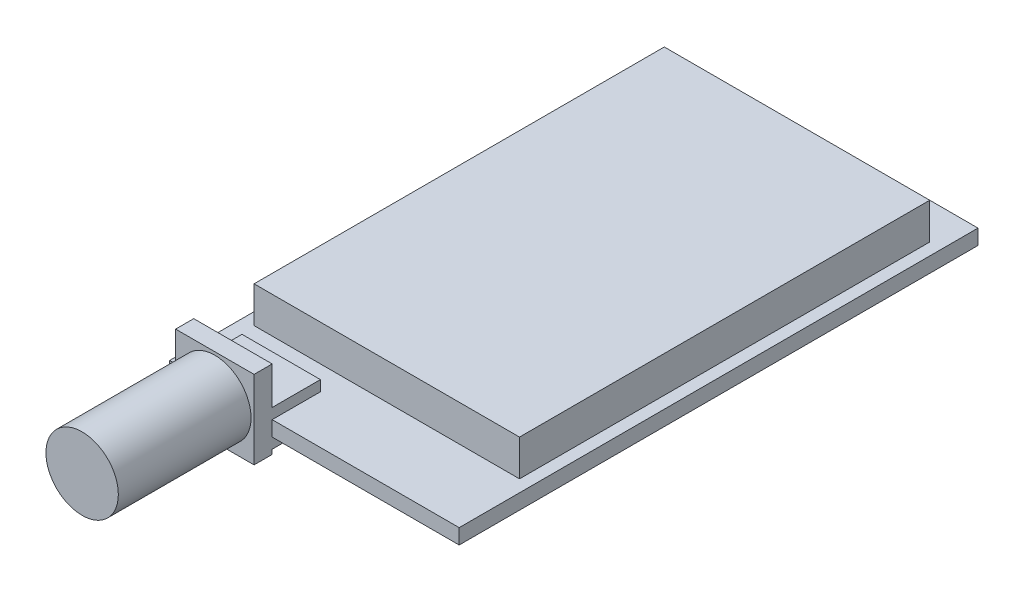
SolidWorks part; units mm, degrees
ref_plane "Front Plane" through (0, 0, 0) normal (0, 0, 1) x (1, 0, 0)
ref_plane "Top Plane" through (0, 0, 0) normal (0, 1, 0) x (1, 0, 0)
ref_plane "Right Plane" through (0, 0, 0) normal (1, 0, 0) x (0, 0, -1)
sketch "Sketch1" plane through (0, 0, 0) normal (0, 1, 0) x (1, 0, 0)
  line L1 (-12, 21.5) -> (12, 21.5)
  line L2 (-12, 21.5) -> (-12, -21.5)
  line L3 (-12, -21.5) -> (12, -21.5)
  line L4 (12, 21.5) -> (12, -21.5)
  line L5 (-12, 21.5) -> (12, -21.5) construction
  line L6 (-12, -21.5) -> (12, 21.5) construction
  point P0 (0, 0)
  dimension "D1" = 43
  dimension "D2" = 24
extrude "PCB" add sketch "Sketch1" along normal blind 1.25
sketch "Sketch2" plane through (0, 1.25, 0) normal (0, 1, 0) x (1, 0, 0)
  line L0 (-12, -21.5) -> (12, -21.5) construction
  line L1 (-11, 18.5) -> (11, 18.5)
  line L2 (-11, 18.5) -> (-11, -15.5)
  line L3 (-11, -15.5) -> (11, -15.5)
  line L4 (11, 18.5) -> (11, -15.5)
  line L5 (-11, 18.5) -> (11, -15.5) construction
  line L6 (-11, -15.5) -> (11, 18.5) construction
  point P0 (0, 1.5)
  dimension "D1" = 34
  dimension "D2" = 22
  dimension "D3" = 6
extrude "RF Casing" add sketch "Sketch2" along normal blind 3
sketch "Sketch3" plane through (0, 0, 21.5) normal (0, 0, 1) x (1, 0, 0)
  line L0 (-12, 1.25) -> (-12, 0) construction
  line L1 (-10, 5.25) -> (-3.5, 5.25)
  line L2 (-10, 5.25) -> (-10, -1.25)
  line L3 (-10, -1.25) -> (-3.5, -1.25)
  line L4 (-3.5, 5.25) -> (-3.5, -1.25)
  line L5 (-10, 5.25) -> (-3.5, -1.25) construction
  line L6 (-10, -1.25) -> (-3.5, 5.25) construction
  line L7 (-11, 1.25) -> (11, 1.25) construction
  point P0 (-6.75, 2)
  dimension "D1" = 2
  dimension "D2" = 6.5
  dimension "D3" = 2.5
extrude "RF Connector Back" add sketch "Sketch3" along normal blind 1.5
sketch "Sketch4" plane through (0, 0, 23) normal (0, 0, 1) x (1, 0, 0)
  line L0 (-10, 5.25) -> (-3.5, -1.25) construction
  circle A0 centre (-6.75, 2) radius 3
  point P11 (-6.75, 2)
  dimension "D1" = 6
extrude "RF Connector Threads" add sketch "Sketch4" along normal blind 11
sketch "Sketch5" plane through (0, 0, 21.5) normal (0, 0, -1) x (-1, 0, 0)
  line L0 (3.5, 5.25) -> (10, 5.25) construction
  line L1 (3.5, 2.125) -> (10, 2.125)
  line L2 (3.5, 2.125) -> (3.5, -0.875)
  line L3 (3.5, -0.875) -> (10, -0.875)
  line L4 (10, 2.125) -> (10, -0.875)
  line L5 (3.5, 2.125) -> (10, -0.875) construction
  line L6 (3.5, -0.875) -> (10, 2.125) construction
  line L7 (3.5, 1.25) -> (3.5, 5.25) construction
  line L8 (12, 1.25) -> (12, 0) construction
  point P0 (6.75, 0.625)
  point P7 (6.75, 5.25)
  point P12 (12, 0.625)
  dimension "D1" = 3
extrude "RF Connector Pins" add sketch "Sketch5" along normal blind 4
